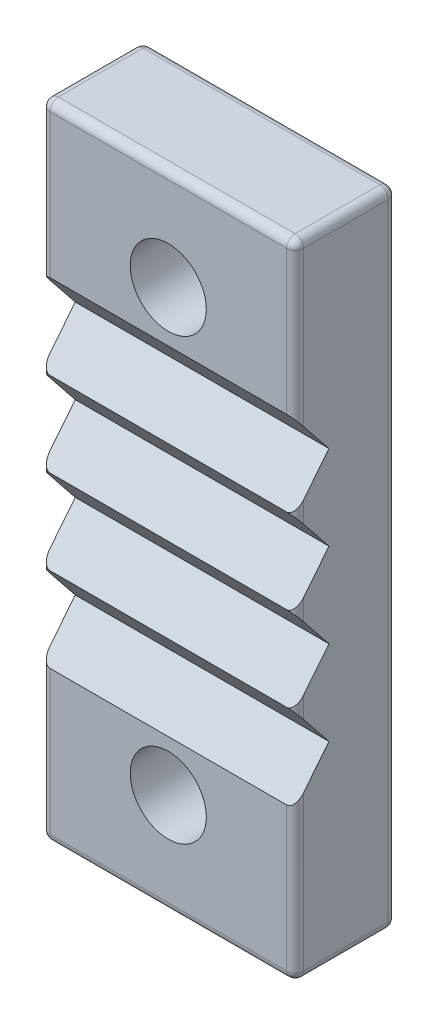
SolidWorks part; units mm, degrees
ref_plane "前视基准面" through (0, 0, 0) normal (0, 0, 1) x (1, 0, 0)
ref_plane "上视基准面" through (0, 0, 0) normal (0, 1, 0) x (1, 0, 0)
ref_plane "右视基准面" through (0, 0, 0) normal (1, 0, 0) x (0, 0, -1)
other "Configuration Table"
sketch "草图1" plane through (0, 0, 0) normal (0, 0, 1) x (1, 0, 0)
  line L0 (0, -13) -> (0, 13) construction
  line L1 (-7.5, -19) -> (7.5, -19)
  line L2 (-7.5, -19) -> (-7.5, 19)
  line L3 (-7.5, 19) -> (7.5, 19)
  line L4 (7.5, -19) -> (7.5, 19)
  line L5 (-7.5, -19) -> (7.5, 19) construction
  line L6 (-7.5, 19) -> (7.5, -19) construction
  circle A0 centre (0, 13) radius 2.25
  circle A1 centre (0, -13) radius 2.25
  point P0 (0, 0)
  point P9 (0, 0)
  dimension "D4" = 4.5
  dimension "D1" = 6
  dimension "D2" = 26
  dimension "D3" = 15
extrude "凸台-拉伸1" add sketch "草图1" along normal mid plane 6
fillet "圆角1" radius 0.5 12 edges at (0, -19, 3) (0, -19, -3) (7.5, -19, 0) (7.5, 0, 3) (7.5, 0, -3) (-7.5, 0, 3) (-7.5, -19, 0) (-7.5, 0, -3) (7.5, 19, 0) (0, 19, 3) (-7.5, 19, 0) (0, 19, -3)
sketch "草图2" plane through (0, 0, 0) normal (1, 0, 0) x (0, 0, -1)
  line L0 (-3, 10) -> (-1, 7.5)
  line L1 (-3, -18.5) -> (-3, 18.5) construction
  line L2 (-1, 7.5) -> (-3, 5)
  line L3 (-3, 5) -> (-3, 10)
  line L4 (-2.5, 19) -> (2.5, 19) construction
  dimension "D1" = 5
  dimension "D2" = 2
  dimension "D3" = 9
extrude "切除-拉伸1" cut sketch "草图2" against normal mid plane 15
pattern_linear "阵列(线性)1" count 4 spacing 5 along (0, -1, 0) of "切除-拉伸1"
